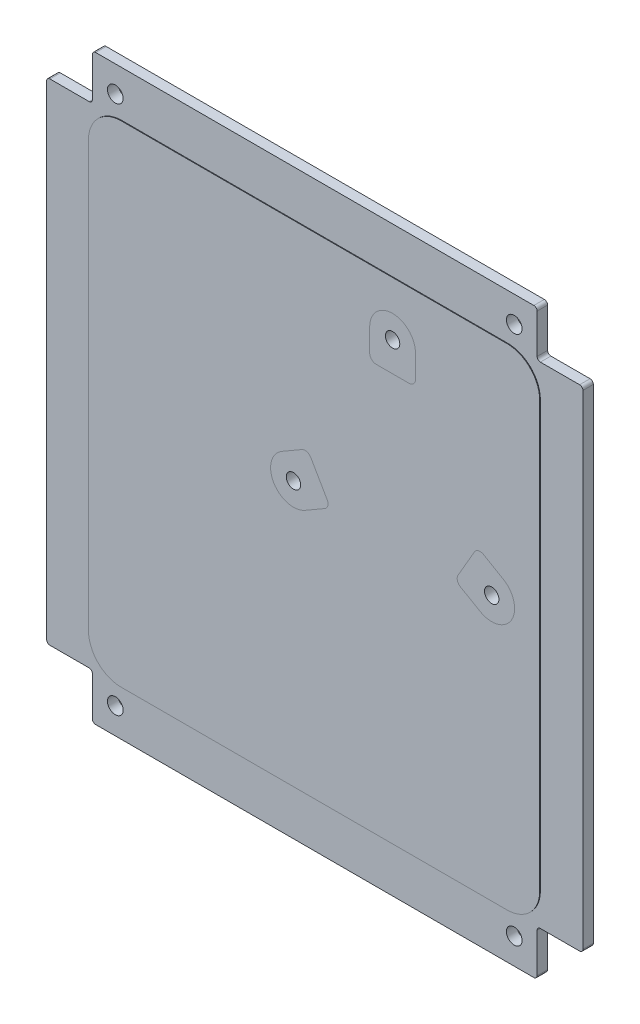
SolidWorks part; units mm, degrees
material "PET"
ref_plane "Front Plane" through (0, 0, 0) normal (0, 0, 1) x (1, 0, 0)
ref_plane "Top Plane" through (0, 0, 0) normal (0, 1, 0) x (1, 0, 0)
ref_plane "Right Plane" through (0, 0, 0) normal (1, 0, 0) x (0, 0, -1)
sketch "Sketch1" plane through (0, 0, 0) normal (0, 0, 1) x (1, 0, 0)
  line L0 (-34, 44) -> (-34, 38)
  line L1 (-33.5, -44.5) -> (33.5, -44.5)
  line L2 (-41, 37) -> (-41, -37)
  line L3 (-33.5, 44.5) -> (33.5, 44.5)
  line L4 (41, -37) -> (41, 37)
  line L5 (34, -44) -> (34, -38)
  line L6 (34.5, -37.5) -> (40.5, -37.5)
  line L7 (-34.5, 37.5) -> (-40.5, 37.5)
  line L8 (34, 44) -> (34, 38)
  line L9 (34.5, 37.5) -> (40.5, 37.5)
  line L10 (-40.5, -37.5) -> (-34.5, -37.5)
  line L11 (-34, -38) -> (-34, -44)
  line L12 (-34.5, -38) -> (34.5, 38) construction
  line L13 (34.5, -38) -> (-34.5, 38) construction
  arc A0 (-33.5, 44.5) -> (-34, 44) centre (-33.5, 44) ccw
  arc A1 (33.5, 44.5) -> (34, 44) centre (33.5, 44) cw
  arc A2 (34, 38) -> (34.5, 37.5) centre (34.5, 38) ccw
  arc A3 (40.5, 37.5) -> (41, 37) centre (40.5, 37) cw
  arc A4 (33.5, -44.5) -> (34, -44) centre (33.5, -44) ccw
  arc A5 (34.5, -37.5) -> (34, -38) centre (34.5, -38) ccw
  arc A6 (40.5, -37.5) -> (41, -37) centre (40.5, -37) ccw
  arc A7 (-34, -44) -> (-33.5, -44.5) centre (-33.5, -44) ccw
  arc A8 (-34, -38) -> (-34.5, -37.5) centre (-34.5, -38) ccw
  arc A9 (-41, -37) -> (-40.5, -37.5) centre (-40.5, -37) ccw
  arc A10 (-40.5, 37.5) -> (-41, 37) centre (-40.5, 37) ccw
  arc A11 (-34.5, 37.5) -> (-34, 38) centre (-34.5, 38) ccw
  point P0 (0, 0)
  dimension "D4" = 0.5
  dimension "D1" = 7
  dimension "D2" = 7
  dimension "D3" = 7
  dimension "D5" = 7
  dimension "D6" = 7
  dimension "D7" = 7
  dimension "D8" = 7
  dimension "D9" = 7
  dimension "D10" = 89
  dimension "D11" = 82
extrude "Boss-Extrude1" add sketch "Sketch1" along normal blind 1.6
sketch "Esboço1" plane through (0, 0, 1.6) normal (0, 0, 1) x (1, 0, 0)
  line L1 (-29.5, -37.5) -> (29.5, -37.5)
  line L2 (-34.5, -32.5) -> (-34.5, 32.5)
  line L3 (-29.5, 37.5) -> (29.5, 37.5)
  line L4 (34.5, -32.5) -> (34.5, 32.5)
  line L5 (-29.5, -32.5) -> (29.5, 32.5) construction
  line L6 (-29.5, 32.5) -> (29.5, -32.5) construction
  arc A0 (-34.5, 32.5) -> (-29.5, 37.5) centre (-29.5, 32.5) cw
  arc A1 (29.5, 37.5) -> (34.5, 32.5) centre (29.5, 32.5) cw
  arc A2 (34.5, -32.5) -> (29.5, -37.5) centre (29.5, -32.5) cw
  arc A3 (-29.5, -37.5) -> (-34.5, -32.5) centre (-29.5, -32.5) cw
  point P0 (0, 0)
  dimension "D1" = 5
  dimension "D2" = 69
  dimension "D3" = 75
extrude "Boss-Extrude2" add sketch "Esboço1" along normal blind 0.1
hole_wizard "M2 Hole1-FixingStructure" positions "Sketch3" profile "Sketch2" hole size "M2" standard "DIN"
sketch "Sketch3" plane through (0, 0, 0) normal (0, 0, -1) x (-1, 0, 0)
  line L0 (-33.5, 44.5) -> (33.5, 44.5) construction
  line L1 (33.5, -44.5) -> (-33.5, -44.5) construction
  line L2 (-41, -37) -> (-41, 37) construction
  line L3 (41, 37) -> (41, -37) construction
  point P0 (-30.5, 40.5)
  point P2 (30.5, 40.5)
  point P4 (-30.5, -40.5)
  point P6 (30.5, -40.5)
  dimension "D1" = 4
  dimension "D2" = 4
  dimension "D3" = 10.5
  dimension "D4" = 10.5
sketch "Sketch2" plane through (30.5, 40.5, 0) normal (1, 0, 0) x (0, 1, 0)
  line L0 (0, 0) -> (0, 200.721)
  line L1 (0, 200.721) -> (1.2, 200)
  line L2 (1.2, 200) -> (1.2, 0)
  line L5 (1.2, 0) -> (0, 0)
  line L10 (0, 200.721) -> (-1.2, 200) construction
  line L11 (0, -6.35) -> (0, 107.95) construction
  dimension "Hole Dia." = 2.4
  dimension "Hole Depth" = 200
  dimension "Drill Angle" = 118
sketch "Sketch4" plane through (0, 0, 1.7) normal (0, 0, 1) x (1, 0, 0)
  line L5 (1.6256, 1.7189) -> (-1.4054, -0.0311)
  line L6 (26.7404, 7.2811) -> (28.9054, 6.0311)
  line L7 (25.4054, -0.0311) -> (23.2404, 1.2189)
  line L8 (25.8744, 7.7811) -> (28.9054, 6.0311)
  line L9 (25.4054, -0.0311) -> (22.3744, 1.7189)
  line L10 (22.0083, 3.0849) -> (24.5083, 7.4151)
  line L11 (22.0083, 3.0849) -> (24.5083, 7.4151)
  line L12 (-4.9054, 6.0311) -> (-1.8744, 7.7811)
  line L13 (-0.5083, 7.4151) -> (1.9917, 3.0849)
  line L14 (8.5, 25.75) -> (8.5, 29.25)
  line L15 (15.5, 29.25) -> (15.5, 25.75)
  line L16 (14.5, 24.75) -> (9.5, 24.75)
  arc A2 (25.8744, 7.7811) -> (24.5083, 7.4151) centre (25.3744, 6.9151) ccw
  arc A3 (25.4054, -0.0311) -> (28.9054, 6.0311) centre (27.1554, 3) ccw
  arc A4 (25.4054, -0.0311) -> (28.9054, 6.0311) centre (27.1554, 3) ccw
  arc A5 (22.3744, 1.7189) -> (22.0083, 3.0849) centre (22.8744, 2.5849) cw
  circle A6 centre (12, 11.75) radius 10 construction
  arc A7 (1.6256, 1.7189) -> (1.9917, 3.0849) centre (1.1256, 2.5849) ccw
  arc A8 (-4.9054, 6.0311) -> (-1.4054, -0.0311) centre (-3.1554, 3) ccw
  arc A9 (-1.8744, 7.7811) -> (-0.5083, 7.4151) centre (-1.3744, 6.9151) cw
  arc A10 (8.5, 25.75) -> (9.5, 24.75) centre (9.5, 25.75) ccw
  arc A11 (15.5, 29.25) -> (8.5, 29.25) centre (12, 29.25) ccw
  arc A12 (15.5, 25.75) -> (14.5, 24.75) centre (14.5, 25.75) cw
  point P13 (12, 11.75)
  point P36 (12, 11.75)
  dimension "D3" = 1
  dimension "D1" = 1
  dimension "D2" = 1
  dimension "D4" = 3
split line "Split Line1"
sketch "Sketch5" plane through (0, 0, 1.7) normal (0, 0, 1) x (1, 0, 0)
  circle A0 centre (27.1554, 3) radius 1.1 construction
  circle A1 centre (12, 29.25) radius 1.1 construction
  circle A2 centre (-3.1554, 3) radius 1.1 construction
  circle A3 centre (27.1554, 3) radius 1.1
  circle A4 centre (12, 29.25) radius 1.1
  circle A5 centre (-3.1554, 3) radius 1.1
extrude "Cut-Extrude1" cut sketch "Sketch5" against normal up to surface (1.7 mm away) up to face at (29.3, 40.5, 0)
